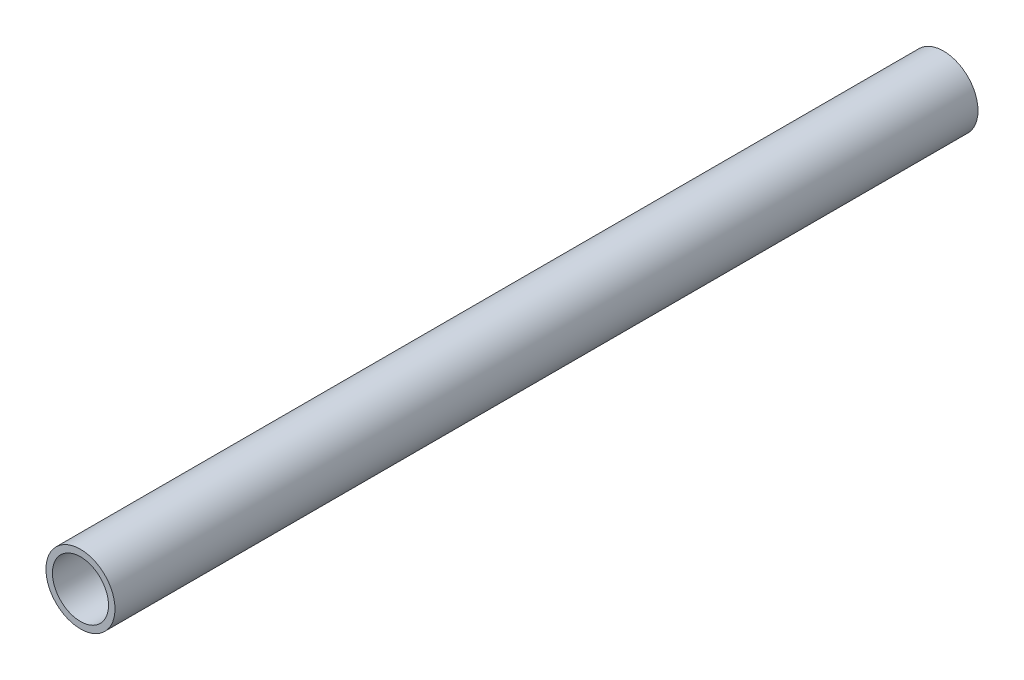
SolidWorks part; units mm, degrees
ref_plane "Alzado" through (0, 0, 0) normal (0, 0, 1) x (1, 0, 0)
ref_plane "Planta" through (0, 0, 0) normal (0, 1, 0) x (1, 0, 0)
ref_plane "Vista lateral" through (0, 0, 0) normal (1, 0, 0) x (0, 0, -1)
sketch "Croquis1" plane through (0, 0, 0) normal (0, 0, 1) x (1, 0, 0)
  circle A0 centre (0, 0) radius 16
  dimension "D1" = 32
extrude "Extruir1" add sketch "Croquis1" along normal mid plane 400
shell "Vaciado1" thickness 3
